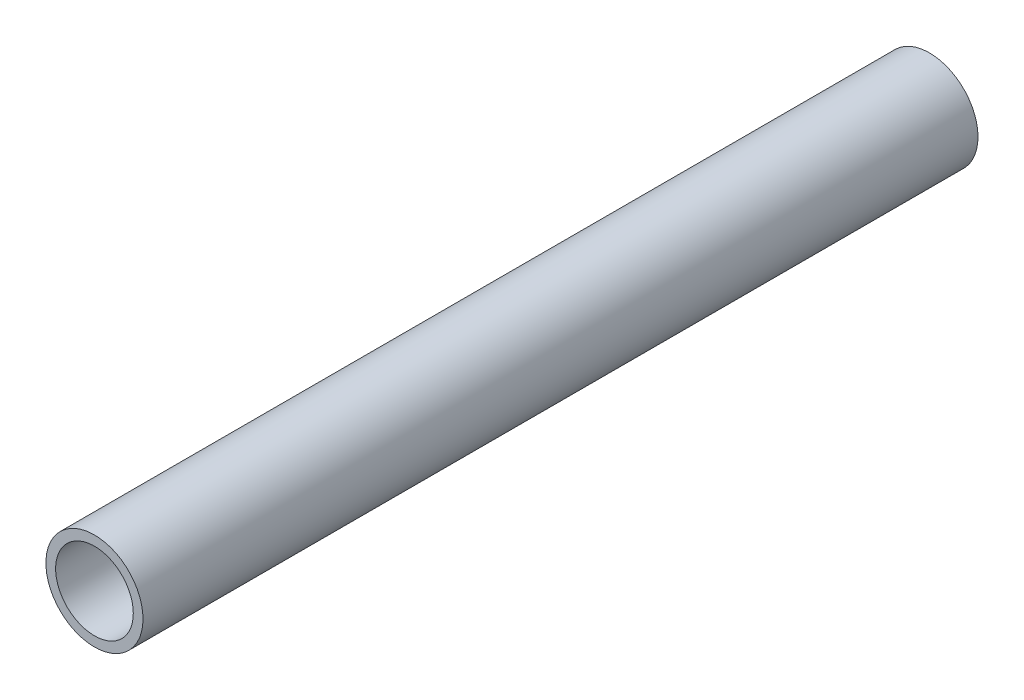
SolidWorks part; units mm, degrees
ref_plane "Front Plane" through (0, 0, 0) normal (0, 0, 1) x (1, 0, 0)
ref_plane "Top Plane" through (0, 0, 0) normal (0, 1, 0) x (1, 0, 0)
ref_plane "Right Plane" through (0, 0, 0) normal (1, 0, 0) x (0, 0, -1)
sketch "Sketch25" plane through (0, 0, 0) normal (0, 0, 1) x (1, 0, 0)
  circle A0 centre (-894.5048, 1142.5831) radius 50
  circle A1 centre (-894.5048, 1142.5831) radius 40
  point P3 (0, 0)
  dimension "D1" = 100
  dimension "D2" = 80
extrude "Boss-Extrude16" add sketch "Sketch25" along normal blind 860
